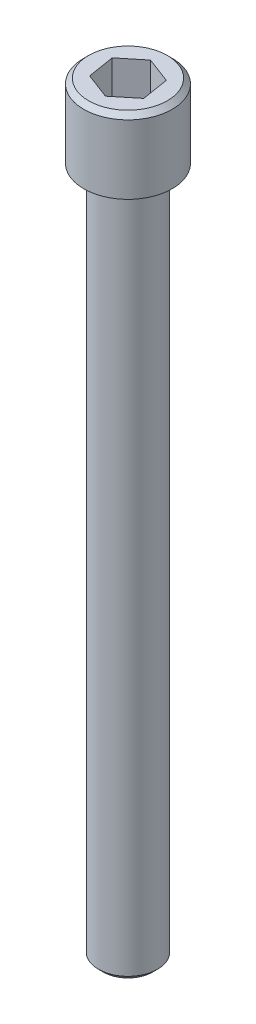
SolidWorks part; units mm, degrees
ref_plane "Přední rovina" through (0, 0, 0) normal (0, 0, 1) x (1, 0, 0)
ref_plane "Horní rovina" through (0, 0, 0) normal (0, 1, 0) x (1, 0, 0)
ref_plane "Pravá rovina" through (0, 0, 0) normal (1, 0, 0) x (0, 0, -1)
sketch "Skica1" plane through (0, 0, 0) normal (0, 1, 0) x (1, 0, 0)
  circle A0 centre (0, 0) radius 1.5
  dimension "D1" = 3
extrude "Přidat vysunutím1" add sketch "Skica1" along normal blind 35
sketch "Skica2" plane through (0, 35, 0) normal (0, 1, 0) x (1, 0, 0)
  circle A0 centre (0, 0) radius 2.25
  dimension "D1" = 4.5
extrude "Přidat vysunutím2" add sketch "Skica2" along normal blind 3.75
sketch "Skica3" plane through (0, 38.75, 0) normal (0, 1, 0) x (1, 0, 0)
  line L1 (-1.0744, -0.875) -> (0.2206, -1.368)
  line L2 (0.2206, -1.368) -> (1.295, -0.493)
  line L3 (1.295, -0.493) -> (1.0744, 0.875)
  line L4 (1.0744, 0.875) -> (-0.2206, 1.368)
  line L5 (-0.2206, 1.368) -> (-1.295, 0.493)
  line L6 (-1.295, 0.493) -> (-1.0744, -0.875)
  circle A0 centre (0, 0) radius 1.2 construction
  dimension "D1" = 2.4
extrude "Odebrat vysunutím1" cut sketch "Skica3" against normal blind 2.25
chamfer "Zkosení1" distance 0.25 angle 45 1 edges at (0, 38.75, 2.25)
chamfer "Zkosení2" distance 0.25 angle 45 1 edges at (0, 0, 1.5)
